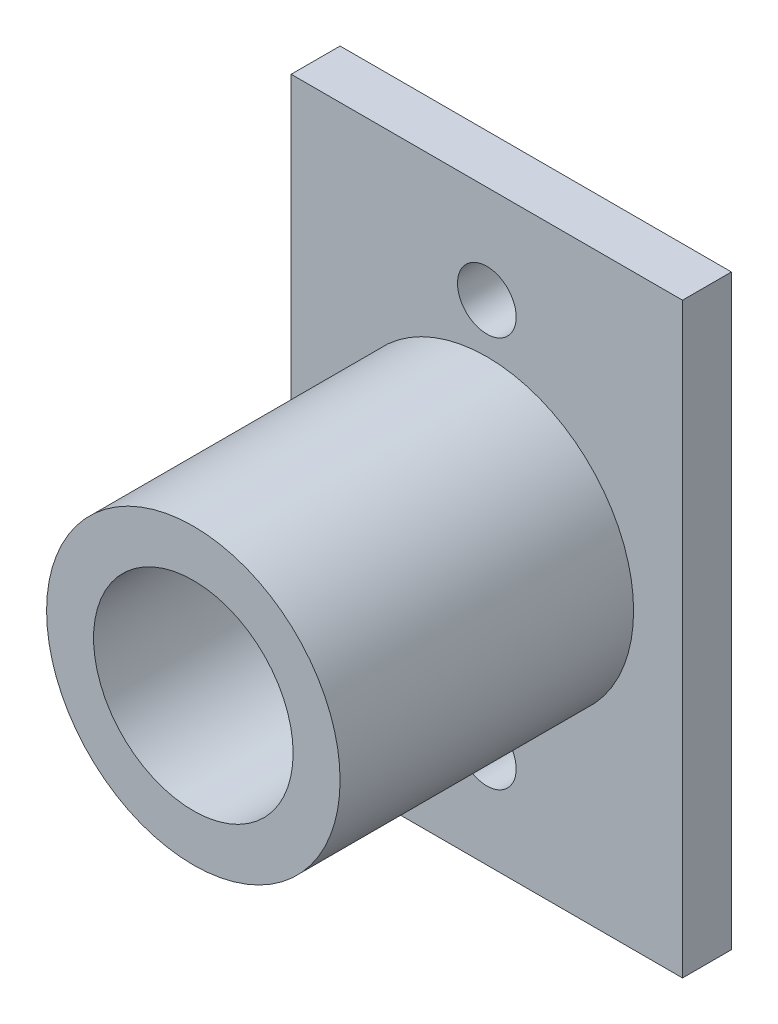
SolidWorks part; units mm, degrees
ref_plane "Front Plane" through (0, 0, 0) normal (0, 0, 1) x (1, 0, 0)
ref_plane "Top Plane" through (0, 0, 0) normal (0, 1, 0) x (1, 0, 0)
ref_plane "Right Plane" through (0, 0, 0) normal (1, 0, 0) x (0, 0, -1)
sketch "Sketch1" plane through (0, 0, 0) normal (0, 0, 1) x (1, 0, 0)
  line L1 (12.7, -19.05) -> (-12.7, -19.05)
  line L2 (12.7, -19.05) -> (12.7, 19.05)
  line L3 (12.7, 19.05) -> (-12.7, 19.05)
  line L4 (-12.7, -19.05) -> (-12.7, 19.05)
  line L5 (12.7, -19.05) -> (-12.7, 19.05) construction
  line L6 (12.7, 19.05) -> (-12.7, -19.05) construction
  point P0 (0, 0)
  dimension "D1" = 25.4
  dimension "D2" = 38.1
extrude "Boss-Extrude1" add sketch "Sketch1" along normal blind 3.175
sketch "Sketch2" plane through (0, 0, 3.175) normal (0, 0, 1) x (1, 0, 0)
  circle A0 centre (0, 0) radius 9.525
  dimension "D1" = 19.05
extrude "Boss-Extrude2" add sketch "Sketch2" along normal blind 19.05
sketch "Sketch3" plane through (0, 0, 22.225) normal (0, 0, 1) x (1, 0, 0)
  circle A0 centre (0, 0) radius 6.477
  dimension "D1" = 12.954
extrude "Cut-Extrude1" cut sketch "Sketch3" against normal through all
sketch "Sketch4" plane through (0, 0, 3.175) normal (0, 0, 1) x (1, 0, 0)
  circle A0 centre (0, 12.7) radius 1.905
  circle A1 centre (0, -12.7) radius 1.905
  dimension "D2" = 3.81
  dimension "D1" = 12.7
  dimension "D3" = 12.7
extrude "Cut-Extrude2" cut sketch "Sketch4" against normal through all
